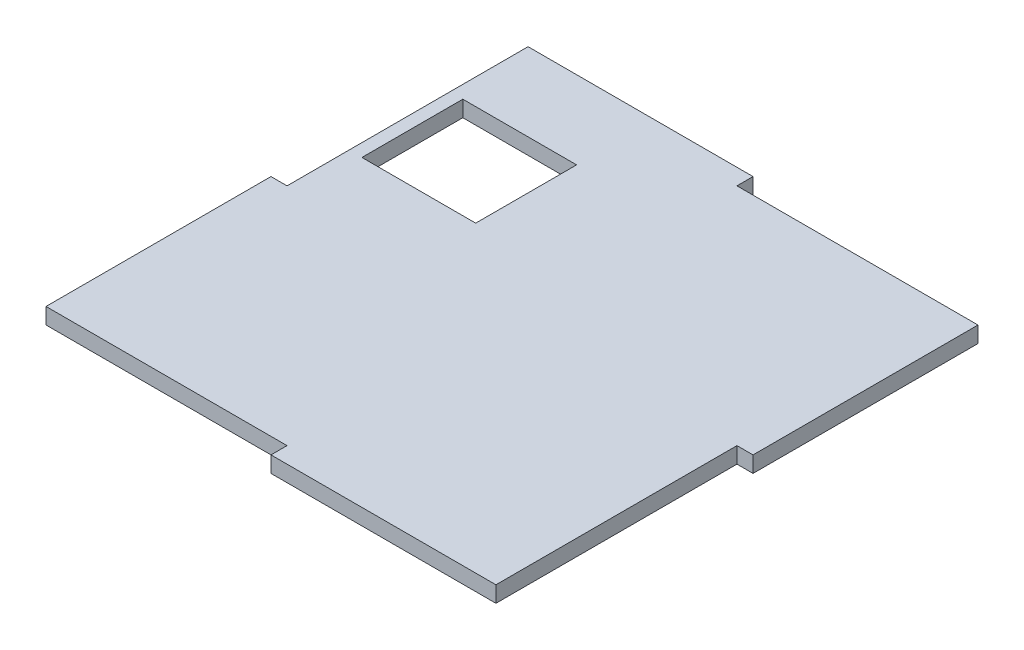
SolidWorks part; units mm, degrees
material "Acrylic (Medium-high impact)"
ref_plane "Front Plane" through (0, 0, 0) normal (0, 0, 1) x (1, 0, 0)
ref_plane "Top Plane" through (0, 0, 0) normal (0, 1, 0) x (1, 0, 0)
ref_plane "Right Plane" through (0, 0, 0) normal (1, 0, 0) x (0, 0, -1)
sketch "Sketch1" plane through (0, 0, 0) normal (0, 1, 0) x (1, 0, 0)
  line L0 (-109.7136, 102.9382) -> (-109.7136, 109.2882)
  line L1 (-109.7136, 102.9382) -> (68.0864, 102.9382)
  line L2 (-109.7136, 102.9382) -> (-109.7136, -74.8618)
  line L3 (-109.7136, -74.8618) -> (68.0864, -74.8618)
  line L4 (68.0864, 102.9382) -> (68.0864, -74.8618)
  line L5 (-109.7136, 109.2882) -> (-20.8136, 109.2882)
  line L6 (-20.8136, 109.2882) -> (-20.8136, 102.9382)
  line L7 (-109.7136, -74.8618) -> (-116.0636, -74.8618)
  line L8 (-116.0636, -74.8618) -> (-116.0636, 14.0382)
  line L9 (-116.0636, 14.0382) -> (-109.7136, 14.0382)
  line L10 (68.0864, -74.8618) -> (68.0864, -81.2118)
  line L11 (68.0864, -81.2118) -> (-20.8136, -81.2118)
  line L12 (-20.8136, -81.2118) -> (-20.8136, -74.8618)
  line L13 (68.0864, 102.9382) -> (74.4364, 102.9382)
  line L14 (74.4364, 102.9382) -> (74.4364, 14.0382)
  line L15 (74.4364, 14.0382) -> (68.0864, 14.0382)
  line L17 (-104.6336, 38.5492) -> (-59.6756, 38.5492)
  line L18 (-104.6336, 38.5492) -> (-104.6336, 78.4272)
  line L19 (-104.6336, 78.4272) -> (-59.6756, 78.4272)
  line L20 (-59.6756, 38.5492) -> (-59.6756, 78.4272)
  line L21 (-104.6336, 38.5492) -> (-59.6756, 78.4272) construction
  line L22 (-104.6336, 78.4272) -> (-59.6756, 38.5492) construction
  point P4 (-20.8136, 102.9382)
  point P5 (-109.7136, 14.0382)
  point P9 (68.0864, 14.0382)
  point P10 (-20.8136, -74.8618)
  point P20 (-82.1546, 58.4882)
  dimension "D1" = 177.8
  dimension "D2" = 177.8
  dimension "D3" = 6.35
  dimension "D4" = 6.35
  dimension "D5" = 6.35
  dimension "D6" = 6.35
  dimension "D7" = 44.45
  dimension "D8" = 5.08
  dimension "D9" = 44.958
  dimension "D10" = 39.878
extrude "Boss-Extrude1" add sketch "Sketch1" along normal blind 6.35 contours L9 L8 L7 L2 | L6 L5 L0 L1 | L4 L1 L2 L3 | L15 L14 L13 L4 | L12 L11 L10 L3
